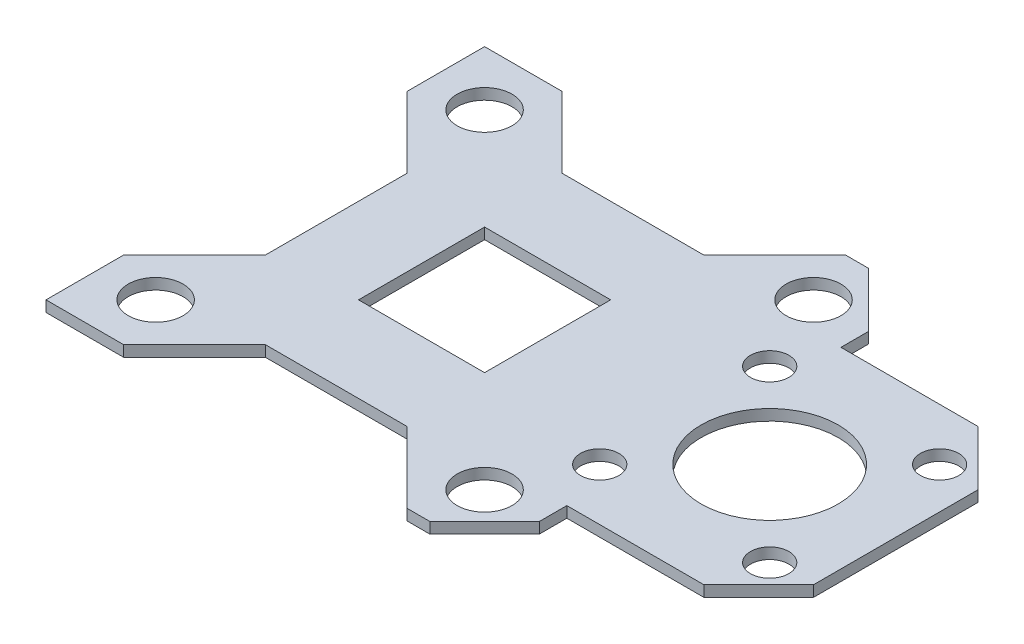
SolidWorks part; units mm, degrees
ref_plane "Front Plane" through (0, 0, 0) normal (0, 0, 1) x (1, 0, 0)
ref_plane "Top Plane" through (0, 0, 0) normal (0, 1, 0) x (1, 0, 0)
ref_plane "Right Plane" through (0, 0, 0) normal (1, 0, 0) x (0, 0, -1)
sketch "Sketch1" plane through (0, 0, 0) normal (0, 1, 0) x (1, 0, 0)
  line L2 (0, 0) -> (0, 80)
  line L12 (80, 0) -> (80, 80)
  line L14 (80, 0) -> (0, 0)
  line L15 (80, 80) -> (0, 80)
  point P0 (0, 0)
  dimension "D1" = 80
  dimension "D2" = 80
extrude "Boss-Extrude1" add sketch "Sketch1" along normal blind 2
sketch "Sketch2" plane through (0, 0, 0) normal (0, -1, 0) x (1, 0, 0)
  line L0 (40, 0) -> (40, -80) construction
  line L1 (80, 0) -> (0, 0) construction
  line L2 (80, -80) -> (0, -80) construction
  line L3 (80, -40) -> (0, -40) construction
  line L4 (30, 0) -> (50, 0) construction
  line L5 (30, 0) -> (30, -80) construction
  line L6 (30, -80) -> (50, -80) construction
  line L7 (50, 0) -> (50, -80) construction
  line L8 (30, 0) -> (50, -80) construction
  line L9 (30, -80) -> (50, 0) construction
  line L10 (10, 0) -> (70, 0) construction
  line L11 (10, 0) -> (10, -80) construction
  line L12 (10, -80) -> (70, -80) construction
  line L13 (70, 0) -> (70, -80) construction
  line L14 (10, 0) -> (70, -80) construction
  line L15 (10, -80) -> (70, 0) construction
  line L16 (80, 0) -> (80, -80) construction
  line L17 (0, 0) -> (0, -80) construction
  circle A0 centre (70, -70) radius 2.5
  circle A1 centre (70, -10) radius 2.5
  circle A2 centre (10, -10) radius 2.5
  circle A3 centre (10, -70) radius 2.5
  point P6 (40, -40)
  point P11 (40, -40)
  dimension "D7" = 5
  dimension "D8" = 5
  dimension "D9" = 5
  dimension "D10" = 5
  dimension "D1" = 20
  dimension "D2" = 60
  dimension "D3" = 30
  dimension "D4" = 60
  dimension "D5" = 30
  dimension "D6" = 60
extrude "Cut-Extrude1" cut sketch "Sketch2" against normal blind 10
sketch "Sketch4" plane through (80, 0, 0) normal (1, 0, 0) x (0, 0, -1)
  line L1 (0, 0) -> (80, 0)
  line L2 (0, 0) -> (0, 2)
  line L3 (0, 2) -> (80, 2)
  line L4 (80, 0) -> (80, 2)
extrude "Boss-Extrude2" add sketch "Sketch4" along normal blind 35
sketch "Sketch3" plane through (0, 0, 0) normal (0, -1, 0) x (1, 0, 0)
  line L0 (0, -40) -> (70, -40) construction
  line L1 (0, 0) -> (0, -80) construction
  line L2 (70, -10) -> (70, -70) construction
  line L4 (114, -18) -> (70, -18) construction
  line L5 (114, -18) -> (114, -62) construction
  line L6 (114, -62) -> (70, -62) construction
  line L7 (70, -18) -> (70, -62) construction
  line L8 (76.5, -24.5) -> (107.5, -24.5) construction
  line L9 (76.5, -24.5) -> (76.5, -55.5) construction
  line L14 (76.5, -55.5) -> (107.5, -55.5) construction
  line L15 (107.5, -24.5) -> (107.5, -55.5) construction
  line L20 (76.5, -24.5) -> (107.5, -55.5) construction
  line L21 (76.5, -55.5) -> (107.5, -24.5) construction
  circle A4 centre (107.5, -24.5) radius 1.5
  circle A5 centre (107.5, -55.5) radius 1.5
  circle A6 centre (76.5, -55.5) radius 1.5
  circle A7 centre (76.5, -24.5) radius 1.5
  circle A8 centre (92, -40) radius 12.5
  point P8 (92, -40)
  point P14 (92, -40)
  point P21 (82, -40)
  dimension "D5" = 3
  dimension "D6" = 3
  dimension "D7" = 3
  dimension "D8" = 3
  dimension "D9" = 25
  dimension "D1" = 44
  dimension "D2" = 44
  dimension "D3" = 31
  dimension "D4" = 31
  dimension "D10" = 22
  dimension "D11" = 22
extrude "Cut-Extrude2" cut sketch "Sketch3" against normal blind 10
sketch "Sketch5" plane through (0, 2, 0) normal (0, 1, 0) x (1, 0, 0)
  line L0 (115, 0) -> (0, 0) construction
  line L1 (0, 80) -> (80, 80)
  line L2 (0, 80) -> (0, 0)
  line L3 (0, 0) -> (80, 0)
  line L4 (80, 80) -> (80, 65.8579)
  line L5 (80, 80) -> (0, 0) construction
  line L6 (0, 80) -> (80, 0) construction
  line L7 (0, 65.8579) -> (12.9289, 52.9289)
  line L8 (65.8579, 80) -> (52.9289, 67.0711)
  line L9 (14.1421, 80) -> (27.0711, 67.0711)
  line L10 (80, 65.8579) -> (67.0711, 52.9289)
  line L11 (72.9289, 87.0711) -> (-7.0711, 7.0711) construction
  line L12 (87.0711, 72.9289) -> (7.0711, -7.0711) construction
  line L13 (7.0711, 87.0711) -> (87.0711, 7.0711) construction
  line L14 (-7.0711, 72.9289) -> (72.9289, -7.0711) construction
  line L15 (12.9289, 27.0711) -> (0, 14.1421)
  line L16 (67.0711, 27.0711) -> (80, 14.1421)
  line L17 (27.0711, 12.9289) -> (14.1421, 0)
  line L18 (52.9289, 12.9289) -> (65.8579, 0)
  line L19 (52.9289, 67.0711) -> (27.0711, 67.0711)
  line L20 (67.0711, 52.9289) -> (67.0711, 27.0711)
  line L21 (52.9289, 12.9289) -> (27.0711, 12.9289)
  line L22 (12.9289, 52.9289) -> (12.9289, 27.0711)
  line L23 (80, 14.1421) -> (80, 0)
  line L24 (28.5, 51.5) -> (51.5, 51.5)
  line L25 (28.5, 51.5) -> (28.5, 28.5)
  line L26 (28.5, 28.5) -> (51.5, 28.5)
  line L27 (51.5, 51.5) -> (51.5, 28.5)
  line L28 (28.5, 51.5) -> (51.5, 28.5) construction
  line L29 (28.5, 28.5) -> (51.5, 51.5) construction
  point P23 (40, 40)
  dimension "D1" = 80
  dimension "D4" = 23
  dimension "D2" = 10
  dimension "D3" = 10
extrude "Cut-Extrude3" cut sketch "Sketch5" against normal blind 10 contours L19 L8 L1 L9 | L27 L24 L25 L26 | L18 L21 L17 L3 | L22 L7 L2 L15
sketch "Sketch6" plane through (0, 2, 0) normal (0, 1, 0) x (1, 0, 0)
  line L0 (0, 65.8579) -> (0, 80) construction
  line L1 (115, 80) -> (80, 80)
  line L2 (115, 80) -> (115, 65)
  line L3 (115, 65) -> (80, 65)
  line L4 (80, 80) -> (80, 65)
  line L5 (115, 0) -> (80, 0)
  line L6 (115, 0) -> (115, 15)
  line L7 (115, 15) -> (80, 15)
  line L8 (80, 0) -> (80, 15)
  line L9 (0, 0) -> (0, 14.1421) construction
  dimension "D1" = 80
  dimension "D2" = 80
  dimension "D3" = 15
  dimension "D4" = 15
extrude "Cut-Extrude4" cut sketch "Sketch6" against normal blind 10
chamfer "Chamfer1" distance 10 angle 45 4 edges at (80, 1, -80) (80, 1, 0) (115, 1, -15) (115, 1, -65)
sketch "Sketch7" plane through (0, 2, 0) normal (0, 1, 0) x (1, 0, 0)
  circle A4 centre (70, 70) radius 5
  circle A5 centre (70, 10) radius 5
  circle A6 centre (10, 10) radius 5
  circle A7 centre (10, 70) radius 5
  dimension "D5" = 10
  dimension "D6" = 10
  dimension "D7" = 10
  dimension "D8" = 10
extrude "Cut-Extrude5" cut sketch "Sketch7" against normal blind 4
sketch "Sketch8" plane through (0, 0, 0) normal (0, -1, 0) x (1, 0, 0)
  circle A0 centre (107.5, -24.5) radius 3.5
  circle A1 centre (107.5, -55.5) radius 3.5
  circle A2 centre (76.5, -55.5) radius 3.5
  circle A3 centre (76.5, -24.5) radius 3.5
  dimension "D1" = 7
  dimension "D2" = 7
  dimension "D3" = 7
  dimension "D4" = 7
extrude "Cut-Extrude6" cut sketch "Sketch8" against normal blind 3
